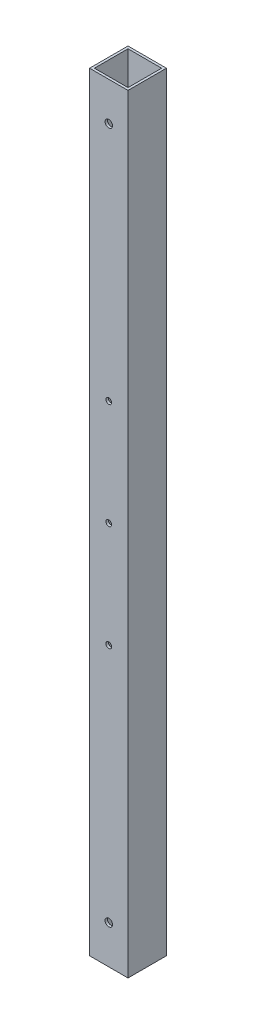
SolidWorks part; units mm, degrees
material "6061-T6 (SS)"
ref_plane "Front Plane" through (0, 0, 0) normal (0, 0, 1) x (1, 0, 0)
ref_plane "Top Plane" through (0, 0, 0) normal (0, 1, 0) x (1, 0, 0)
ref_plane "Right Plane" through (0, 0, 0) normal (1, 0, 0) x (0, 0, -1)
sketch "Sketch1" plane through (0, 0, 0) normal (0, 1, 0) x (1, 0, 0)
  line L0 (11.1125, 11.1125) -> (-11.1125, 11.1125)
  line L1 (12.7, -12.7) -> (-12.7, -12.7)
  line L2 (12.7, -12.7) -> (12.7, 12.7)
  line L3 (12.7, 12.7) -> (-12.7, 12.7)
  line L4 (-12.7, -12.7) -> (-12.7, 12.7)
  line L5 (12.7, -12.7) -> (-12.7, 12.7) construction
  line L6 (12.7, 12.7) -> (-12.7, -12.7) construction
  line L7 (-11.1125, -11.1125) -> (-11.1125, 11.1125)
  line L8 (11.1125, -11.1125) -> (-11.1125, -11.1125)
  line L9 (11.1125, -11.1125) -> (11.1125, 11.1125)
  point P0 (0, 0)
  dimension "D1" = 25.4
  dimension "D2" = 25.4
  dimension "D3" = 1.5875
extrude "Boss-Extrude1" add sketch "Sketch1" along normal mid plane 508
sketch "Sketch2" plane through (0, 0, -12.7) normal (0, 0, -1) x (-1, 0, 0)
  line L0 (-12.7, 254) -> (12.7, 254) construction
  line L1 (12.7, 254) -> (12.7, -254) construction
  line L2 (-12.7, -254) -> (12.7, -254) construction
  point P0 (0, 228.6)
  point P1 (0, -228.6)
  point P3 (0, 254)
  point P8 (0, -254)
  dimension "D1" = 25.4
  dimension "D2" = 12.7
  dimension "D3" = 25.4
  dimension "D4" = 12.7
hole_wizard "#10 (0.1935) Diameter Hole1" positions "Sketch4" profile "Sketch3" hole size "#10" standard "ANSI Inch"
sketch "Sketch4" plane through (0, 0, -12.7) normal (0, 0, -1) x (-1, 0, 0)
  point P0 (0, 228.6)
  point P3 (0, -228.6)
sketch "Sketch3" plane through (0, 228.6, -12.7) normal (1, 0, 0) x (0, 1, 0)
  line L0 (0, 0) -> (0, 52.2766)
  line L1 (0, 52.2766) -> (2.4574, 50.8)
  line L2 (2.4574, 50.8) -> (2.4574, 0)
  line L5 (2.4574, 0) -> (0, 0)
  line L10 (0, 52.2766) -> (-2.4575, 50.8) construction
  line L11 (0, -6.35) -> (0, 107.95) construction
  dimension "Hole Dia." = 4.9149
  dimension "Hole Depth" = 50.8
  dimension "Drill Angle" = 118
sketch "Sketch6" plane through (0, 0, 12.7) normal (0, 0, 1) x (1, 0, 0)
  circle A0 centre (0, -69.85) radius 1.905
  circle A1 centre (0, 0) radius 1.905
  circle A2 centre (0, 69.85) radius 1.905
  dimension "D1" = 3.81
  dimension "D2" = 158.75
  dimension "D3" = 3
extrude "Cut-Extrude1" cut sketch "Sketch6" against normal through all
